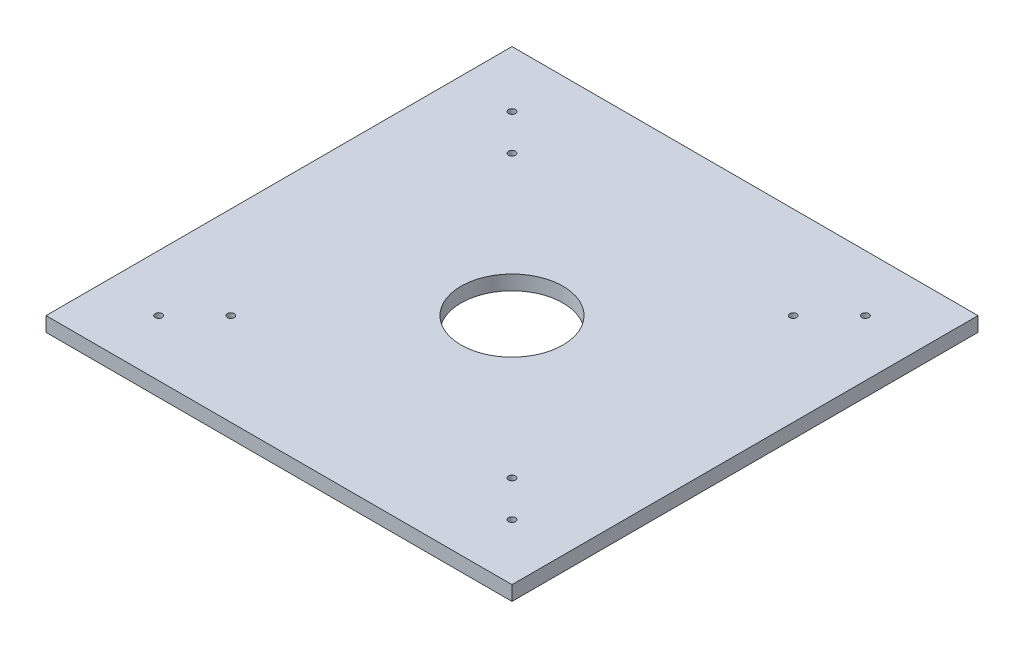
SolidWorks part; units mm, degrees
ref_plane "Front Plane" through (0, 0, 0) normal (0, 0, 1) x (1, 0, 0)
ref_plane "Top Plane" through (0, 0, 0) normal (0, 1, 0) x (1, 0, 0)
ref_plane "Right Plane" through (0, 0, 0) normal (1, 0, 0) x (0, 0, -1)
sketch "Sketch1" plane through (0, 0, 0) normal (0, 1, 0) x (1, 0, 0)
  line L0 (0, 80) -> (0, -80) construction
  line L1 (-80, -80) -> (80, -80)
  line L2 (-80, -80) -> (-80, 80)
  line L3 (-80, 80) -> (80, 80)
  line L4 (80, -80) -> (80, 80)
  line L5 (-80, -80) -> (80, 80) construction
  line L6 (-80, 80) -> (80, -80) construction
  line L7 (-80, 0) -> (80, 0) construction
  circle A0 centre (-60.6642, 60.6642) radius 1.2
  circle A1 centre (-48.2796, 48.2796) radius 1.2
  circle A2 centre (48.2796, 48.2796) radius 1.2
  circle A3 centre (60.6642, 60.6642) radius 1.2
  circle A4 centre (60.6642, -60.6642) radius 1.2
  circle A5 centre (48.2796, -48.2796) radius 1.2
  circle A6 centre (-48.2796, -48.2796) radius 1.2
  circle A7 centre (-60.6642, -60.6642) radius 1.2
  circle A8 centre (0, 0) radius 17.5
  point P0 (0, 0)
  dimension "D2" = 2.4
  dimension "D3" = 2.4
  dimension "D4" = 35
  dimension "D1" = 160
extrude "Boss-Extrude1" add sketch "Sketch1" along normal blind 5
